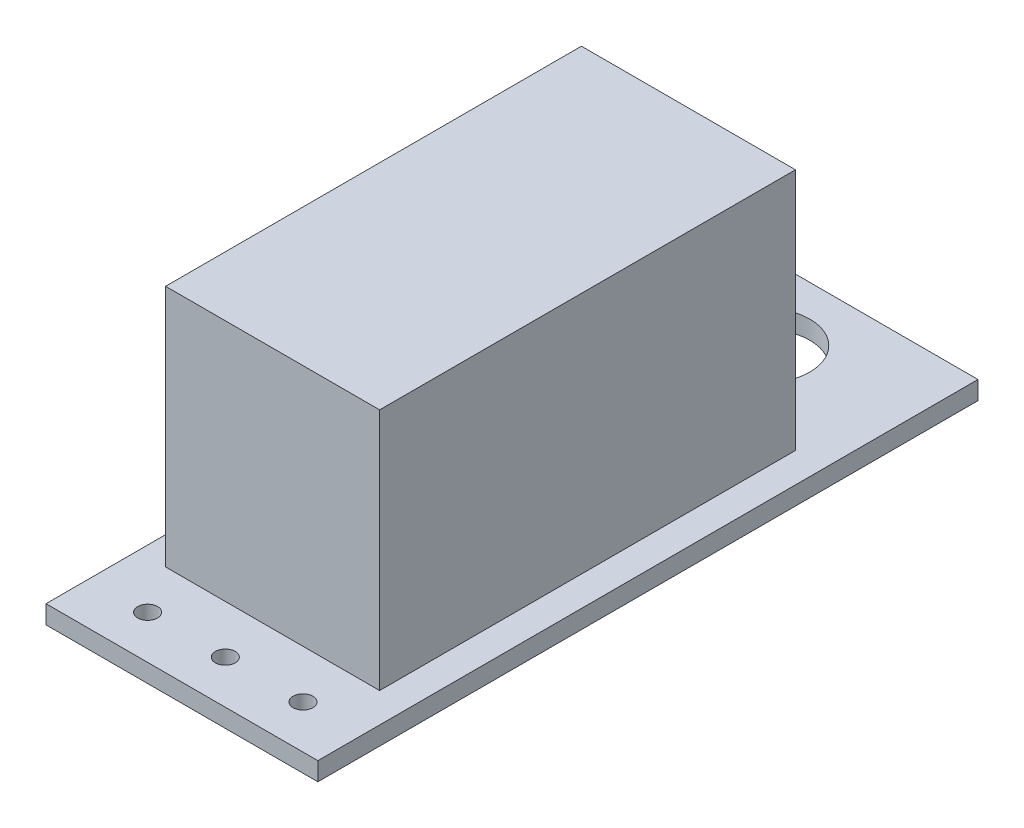
SolidWorks part; units mm, degrees
ref_plane "Front Plane" through (0, 0, 0) normal (0, 0, 1) x (1, 0, 0)
ref_plane "Top Plane" through (0, 0, 0) normal (0, 1, 0) x (1, 0, 0)
ref_plane "Right Plane" through (0, 0, 0) normal (1, 0, 0) x (0, 0, -1)
sketch "Sketch1" plane through (0, 0, 0) normal (0, 1, 0) x (1, 0, 0)
  line L1 (-3.5, -6.8) -> (3.5, -6.8)
  line L2 (-3.5, -6.8) -> (-3.5, 6.8)
  line L3 (-3.5, 6.8) -> (3.5, 6.8)
  line L4 (3.5, -6.8) -> (3.5, 6.8)
  line L5 (-3.5, -6.8) -> (3.5, 6.8) construction
  line L6 (-3.5, 6.8) -> (3.5, -6.8) construction
  point P0 (0, 0)
  dimension "D1" = 13.6
  dimension "D2" = 7
extrude "Boss-Extrude1" add sketch "Sketch1" along normal blind 7.95
sketch "Sketch2" plane through (0, 0, 0) normal (0, -1, 0) x (1, 0, 0)
  line L1 (-4.4156, 9.7954) -> (4.4744, 9.7954)
  line L2 (-4.4156, 9.7954) -> (-4.4156, -11.7946)
  line L3 (-4.4156, -11.7946) -> (4.4744, -11.7946)
  line L4 (4.4744, 9.7954) -> (4.4744, -11.7946)
  line L5 (-4.4156, 9.7954) -> (4.4744, -11.7946) construction
  line L6 (-4.4156, -11.7946) -> (4.4744, 9.7954) construction
  circle A0 centre (0.015, -9.2546) radius 1.5
  circle A1 centre (0.0294, 8.3766) radius 0.325
  circle A2 centre (2.5694, 8.3766) radius 0.325
  circle A3 centre (-2.5106, 8.3766) radius 0.325
  point P0 (0.0294, -0.9996)
  dimension "D3" = 3
  dimension "D6" = 0.65
  dimension "D7" = 0.65
  dimension "D8" = 0.65
  dimension "D1" = 21.59
  dimension "D2" = 8.89
  dimension "D4" = 19.05
  dimension "D5" = 1
  dimension "D9" = 2.54
  dimension "D10" = 2.54
  dimension "D11" = 0
extrude "Boss-Extrude2" add sketch "Sketch2" along normal blind 0.6
